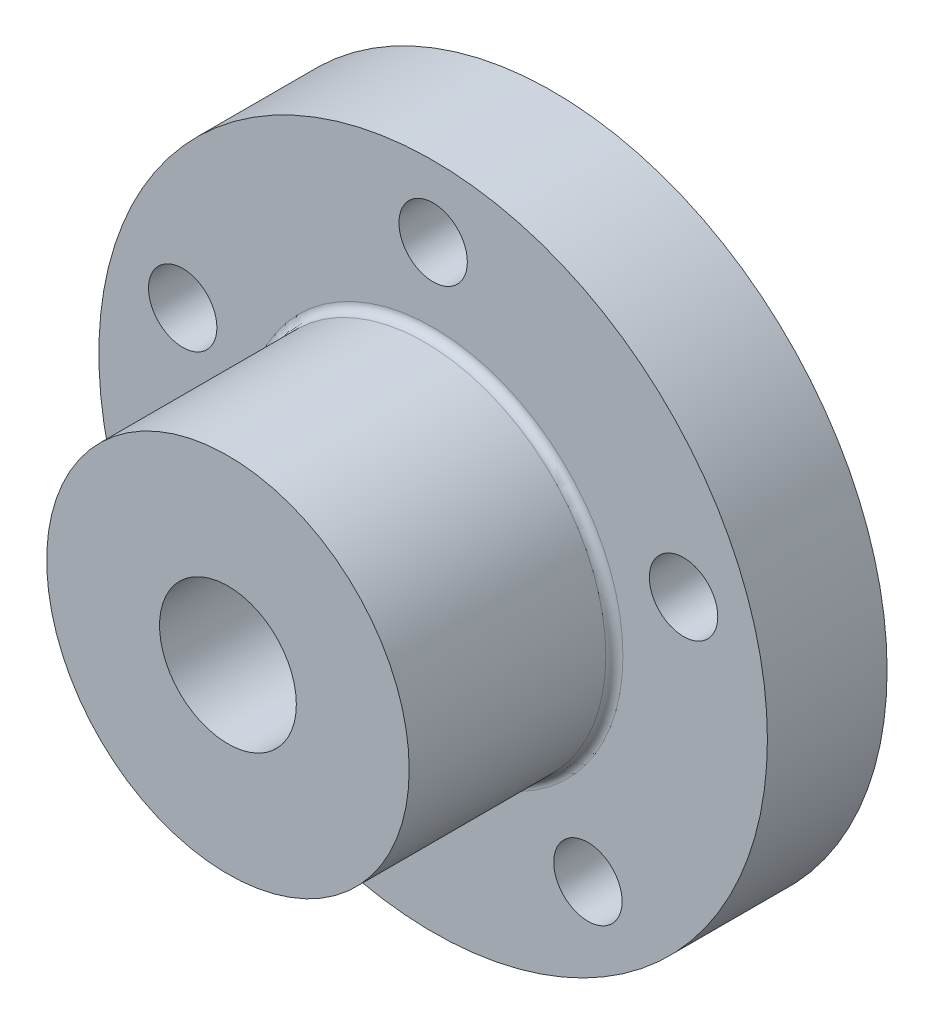
SolidWorks part; units mm, degrees
ref_plane "Спереди" through (0, 0, 0) normal (0, 0, 1) x (1, 0, 0)
ref_plane "Сверху" through (0, 0, 0) normal (0, 1, 0) x (1, 0, 0)
ref_plane "Справа" through (0, 0, 0) normal (1, 0, 0) x (0, 0, -1)
sketch "Эскиз1" plane through (0, 0, 0) normal (0, 0, 1) x (1, 0, 0)
  circle A0 centre (0, 0) radius 19.55
extrude "Вытянуть1" add sketch "Эскиз1" along normal blind 7
sketch "Эскиз2" plane through (0, 0, 7) normal (0, 0, 1) x (1, 0, 0)
  circle A0 centre (0, 0) radius 10.6
extrude "Вытянуть2" add sketch "Эскиз2" along normal blind 12
fillet "Скругление1" radius 0.5 1 edges at (10.6, 0, 7)
sketch "Эскиз3" plane through (0, 0, 19) normal (0, 0, 1) x (1, 0, 0)
  circle A0 centre (0, 0) radius 4
extrude "Вытянуть3" cut sketch "Эскиз3" against normal through all
sketch "Эскиз4" plane through (0, 0, 7) normal (0, 0, 1) x (1, 0, 0)
  circle A2 centre (0, 0) radius 15.4 construction
  circle A3 centre (0, 15.4) radius 2
  circle A4 centre (14.6463, 4.7589) radius 2
  circle A5 centre (9.0519, -12.4589) radius 2
  circle A6 centre (-9.0519, -12.4589) radius 2
  circle A7 centre (-14.6463, 4.7589) radius 2
extrude "Вытянуть4" cut sketch "Эскиз4" against normal through all
